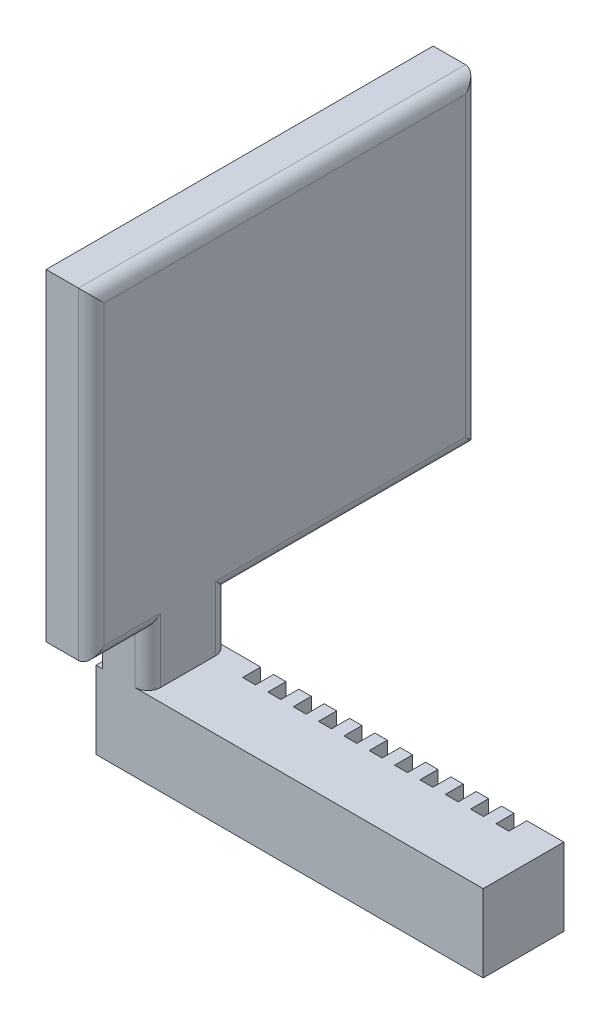
SolidWorks part; units mm, degrees
material "6061-T4 (SS)"
ref_plane "Front Plane" through (0, 0, 0) normal (0, 0, 1) x (1, 0, 0)
ref_plane "Top Plane" through (0, 0, 0) normal (0, 1, 0) x (1, 0, 0)
ref_plane "Right Plane" through (0, 0, 0) normal (1, 0, 0) x (0, 0, -1)
sketch "Sketch2" plane through (0, 0, 0) normal (1, 0, 0) x (0, 0, -1)
  line L1 (-30, -25) -> (30, -25)
  line L2 (-30, -25) -> (-30, 25)
  line L3 (-30, 25) -> (30, 25)
  line L4 (30, -25) -> (30, 25)
  line L5 (-30, -25) -> (30, 25) construction
  line L6 (-30, 25) -> (30, -25) construction
  point P0 (0, 0)
  dimension "D1" = 60
  dimension "D2" = 50
extrude "Boss-Extrude1" add sketch "Sketch2" along normal mid plane 8
sketch "Sketch3" plane through (0, -25, 0) normal (0, -1, 0) x (1, 0, 0)
  line L1 (-4, 21.25) -> (4, 21.25)
  line L2 (-4, 21.25) -> (-4, 8.75)
  line L3 (-4, 8.75) -> (4, 8.75)
  line L4 (4, 21.25) -> (4, 8.75)
  line L5 (-4, 21.25) -> (4, 8.75) construction
  line L6 (-4, 8.75) -> (4, 21.25) construction
  line L9 (0, 30) -> (0, -30) construction
  point P0 (0, 15)
  dimension "D1" = 12.5
  dimension "D2" = 8
  dimension "D3" = 15
extrude "Boss-Extrude2" add sketch "Sketch3" along normal blind 20
fillet "Fillet2" radius 2 8 edges at (4, -25, -10.625) (4, -35, 8.75) (4, -45, 15) (4, -35, 21.25) (4, -25, 25.625) (4, 0, 30) (4, 25, 0) (4, 0, -30)
chamfer "Chamfer2" distance 1 angle 45 2 edges at (-4, 25, 0) (-4, 0, -30)
sketch "Sketch4" plane through (0, -45, 0) normal (0, -1, 0) x (1, 0, 0)
  line L1 (-4, 21.25) -> (56, 21.25)
  line L2 (-4, 21.25) -> (-4, 8.75)
  line L3 (-4, 8.75) -> (56, 8.75)
  line L4 (56, 21.25) -> (56, 8.75)
  dimension "D1" = 60
  dimension "D2" = 12.5
  dimension "D3" = 4
  dimension "D4" = 8.75
extrude "Boss-Extrude4" add sketch "Sketch4" against normal blind 12
sketch "Sketch10" plane through (0, -33, 0) normal (0, 1, 0) x (1, 0, 0)
  line L0 (-4, -8.75) -> (56, -8.75) construction
  line L1 (9, -8.75) -> (11, -8.75)
  line L2 (9, -8.75) -> (9, -11.55)
  line L3 (9, -11.55) -> (11, -11.55)
  line L4 (11, -8.75) -> (11, -11.55)
  line L5 (2, 30) -> (2, -8.75) construction
  dimension "D1" = 2
  dimension "D2" = 2.8
  dimension "D3" = 7
extrude "Cut-Extrude1" cut sketch "Sketch10" against normal through all both and the other way through all
pattern_linear "LPattern5" count 11 spacing 3.927 along (1, 0, 0) of "Cut-Extrude1"
